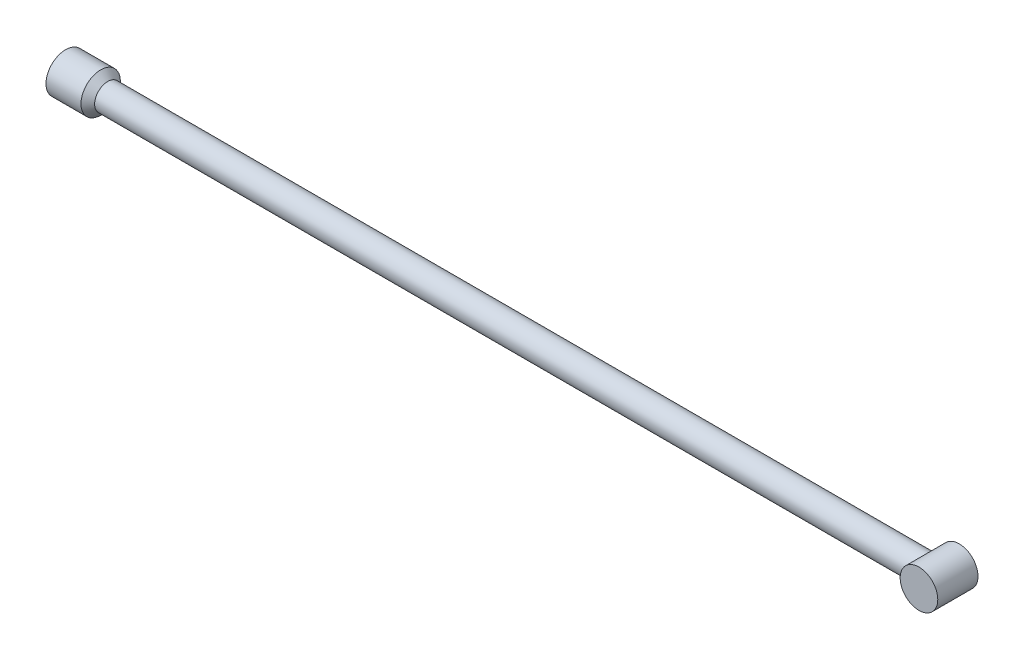
SolidWorks part; units mm, degrees
ref_plane "Front Plane" through (0, 0, 0) normal (0, 0, 1) x (1, 0, 0)
ref_plane "Top Plane" through (0, 0, 0) normal (0, 1, 0) x (1, 0, 0)
ref_plane "Right Plane" through (0, 0, 0) normal (1, 0, 0) x (0, 0, -1)
sketch "Sketch2" plane through (0, 0, 0) normal (1, 0, 0) x (0, 0, -1)
  circle A0 centre (0, 0) radius 75
  circle A1 centre (0, 0) radius 37.5
  dimension "D1" = 150
  dimension "D2" = 75
extrude "Boss-Extrude1" add sketch "Sketch2" along normal blind 4750
sketch "Sketch3" plane through (0, 0, 0) normal (-1, 0, 0) x (0, 0, 1)
  circle A0 centre (0, 0) radius 112.5
  circle A1 centre (0, 0) radius 92.5
  dimension "D1" = 225
  dimension "D2" = 185
extrude "Boss-Extrude2" add sketch "Sketch3" along normal blind 200
sketch "Sketch4" plane through (0, 0, 0) normal (0, 0, 1) x (1, 0, 0)
  circle A0 centre (4795.7962, 0) radius 107.5
  circle A1 centre (4795.7962, 0) radius 92.5
  dimension "D1" = 215
  dimension "D2" = 185
extrude "Boss-Extrude9" add sketch "Sketch4" along normal through all and the other way through all separate body
sketch "Sketch5" plane through (0, 0, 112.5) normal (0, 0, 1) x (1, 0, 0)
  circle A0 centre (4795.7962, 0) radius 75
extrude "Cut-Extrude1" cut sketch "Sketch5" against normal blind 175
sketch "Sketch6" plane through (0, 0, 0) normal (-1, 0, 0) x (0, 0, 1)
  circle A0 centre (0, 0) radius 37.5
extrude "Cut-Extrude2" cut sketch "Sketch6" against normal blind 4787
sketch "Sketch7" plane through (0, 0, 0) normal (0, 0, 1) x (1, 0, 0)
  line L0 (0, 112.5) -> (0, 75)
  line L1 (0, 75) -> (40.4361, 75)
  line L2 (4750, 75) -> (0, 75) construction
  line L3 (40.4361, 75) -> (0, 112.5)
  line L4 (-224.7945, 0) -> (133.1421, 0) construction
revolve "Revolve1" add sketch "Sketch7" angle 360 about L4
sketch "Sketch9" plane through (0, 0, 112.5) normal (0, 0, 1) x (1, 0, 0)
  circle A0 centre (4795.7962, 0) radius 107.5
  dimension "D1" = 215
extrude "Boss-Extrude10" add sketch "Sketch9" along normal blind 5 and the other way blind 5
sketch "Sketch10" plane through (0, 0, -112.5) normal (0, 0, -1) x (-1, 0, 0)
  circle A0 centre (-4797.3895, 0) radius 91.2408
extrude "Cut-Extrude3" cut sketch "Sketch10" against normal blind 181
